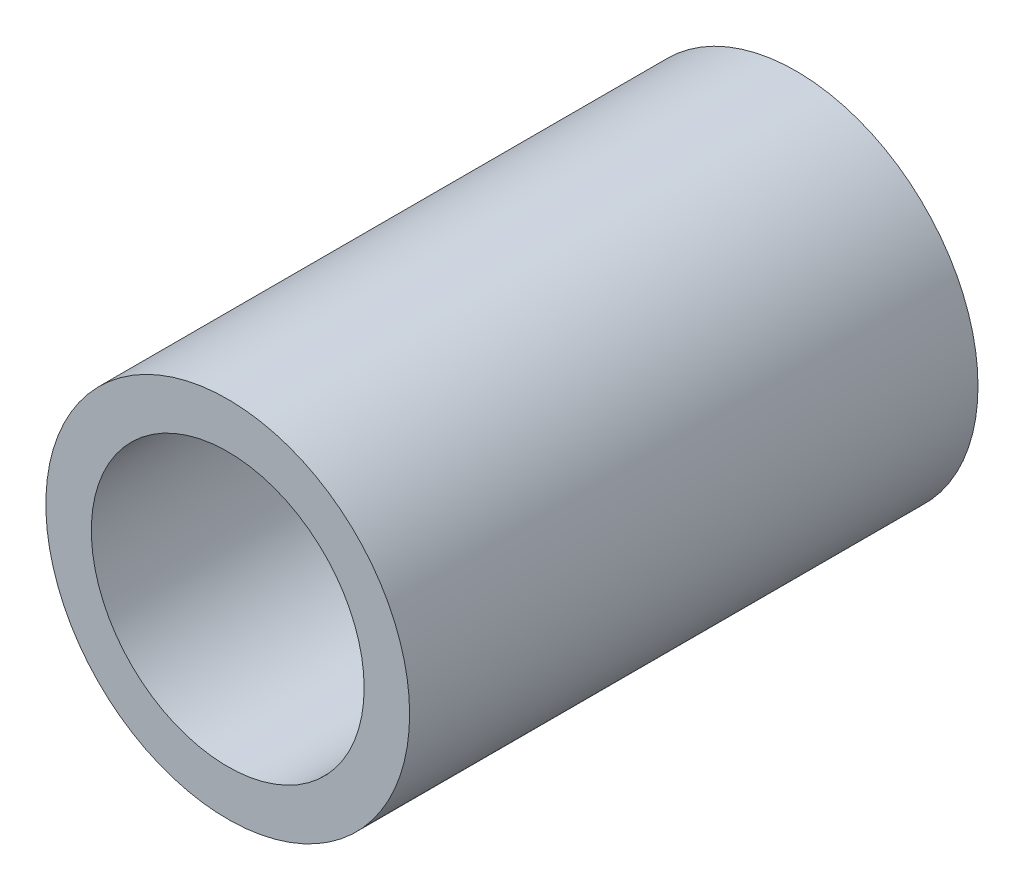
SolidWorks part; units mm, degrees
material "Ouro puro"
ref_plane "Plano frontal" through (0, 0, 0) normal (0, 0, 1) x (1, 0, 0)
ref_plane "Plano superior" through (0, 0, 0) normal (0, 1, 0) x (1, 0, 0)
ref_plane "Plano direito" through (0, 0, 0) normal (1, 0, 0) x (0, 0, -1)
sketch "Esboço1" plane through (0, 0, 0) normal (0, 0, 1) x (1, 0, 0)
  circle A0 centre (0, 0) radius 8
  circle A1 centre (0, 0) radius 6
  dimension "D1" = 16
  dimension "D2" = 12
extrude "Ressalto-extrusão1" add sketch "Esboço1" along normal blind 25
